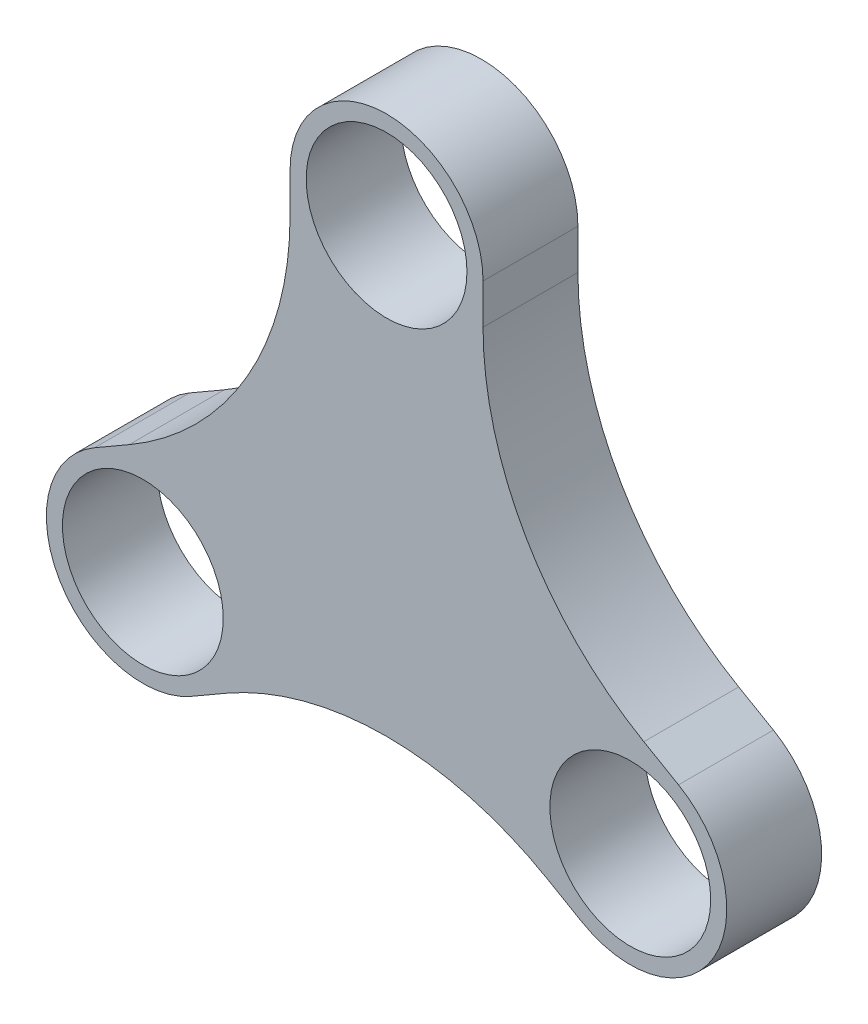
SolidWorks part; units mm, degrees
ref_plane "前视基准面" through (0, 0, 0) normal (0, 0, 1) x (1, 0, 0)
ref_plane "上视基准面" through (0, 0, 0) normal (0, 1, 0) x (1, 0, 0)
ref_plane "右视基准面" through (0, 0, 0) normal (1, 0, 0) x (0, 0, -1)
other "Configuration Table"
sketch "草图1" plane through (0, 0, 0) normal (0, 0, 1) x (1, 0, 0)
  line L0 (0, 0) -> (0, 150) construction
  line L1 (0, 0) -> (-129.9038, -75) construction
  line L2 (0, 0) -> (129.9038, -75) construction
  line L3 (-60, 150.1111) -> (-60, 175)
  line L4 (60, 150.1111) -> (60, 175)
  line L5 (160, -23.094) -> (181.5544, -35.5385)
  line L6 (100, -127.0171) -> (121.5544, -139.4615)
  line L7 (-100, -127.0171) -> (-121.5544, -139.4615)
  line L8 (-160, -23.094) -> (-181.5544, -35.5385)
  arc A0 (-60, 175) -> (60, 175) centre (0, 175) cw
  arc A1 (181.5544, -35.5385) -> (121.5544, -139.4615) centre (151.5544, -87.5) cw
  arc A2 (-121.5544, -139.4615) -> (-181.5544, -35.5385) centre (-151.5544, -87.5) cw
  arc A3 (-100, -127.0171) -> (100, -127.0171) centre (0, -300.2221) cw
  arc A4 (160, -23.094) -> (60, 150.1111) centre (260, 150.1111) cw
  arc A5 (-60, 150.1111) -> (-160, -23.094) centre (-260, 150.1111) cw
  point P10 (-12.1992, -62.5964)
  point P12 (0, -86.7312)
  point P23 (0, 0)
  point P24 (60, 34.641)
  point P27 (-60, 34.641)
  dimension "D5" = 175
  dimension "D7" = 200
  dimension "D8" = 200
  dimension "D1" = 120
  dimension "D2" = 120
  dimension "D3" = 150
  dimension "D4" = 60
  dimension "D6" = 3
extrude "凸台-拉伸1" add sketch "草图1" along normal blind 59
sketch "草图2" plane through (0, 0, 59) normal (0, 0, 1) x (1, 0, 0)
  line L0 (0, 0) -> (0, 179.3893) construction
  line L1 (0, 0) -> (-243.2634, -140.4482) construction
  line L2 (0, 0) -> (231.6951, -133.7692) construction
  arc A1 (121.5544, -139.4615) -> (181.5544, -35.5385) centre (151.5544, -87.5) ccw construction
  arc A2 (60, 175) -> (-60, 175) centre (0, 175) ccw construction
  arc A3 (-181.5544, -35.5385) -> (-121.5544, -139.4615) centre (-151.5544, -87.5) ccw construction
  arc A4 (121.5544, -139.4615) -> (181.5544, -35.5385) centre (151.5544, -87.5) ccw construction
  arc A5 (60, 175) -> (-60, 175) centre (0, 175) ccw construction
  arc A6 (-181.5544, -35.5385) -> (-121.5544, -139.4615) centre (-151.5544, -87.5) ccw construction
  circle A7 centre (-151.5544, -87.5) radius 50
  circle A8 centre (0, 175) radius 50
  circle A9 centre (151.5544, -87.5) radius 50
  dimension "D3" = 100
  dimension "D4" = 100
  dimension "D5" = 100
  dimension "D1" = 60
  dimension "D2" = 60
extrude "切除-拉伸1" cut sketch "草图2" against normal through all
